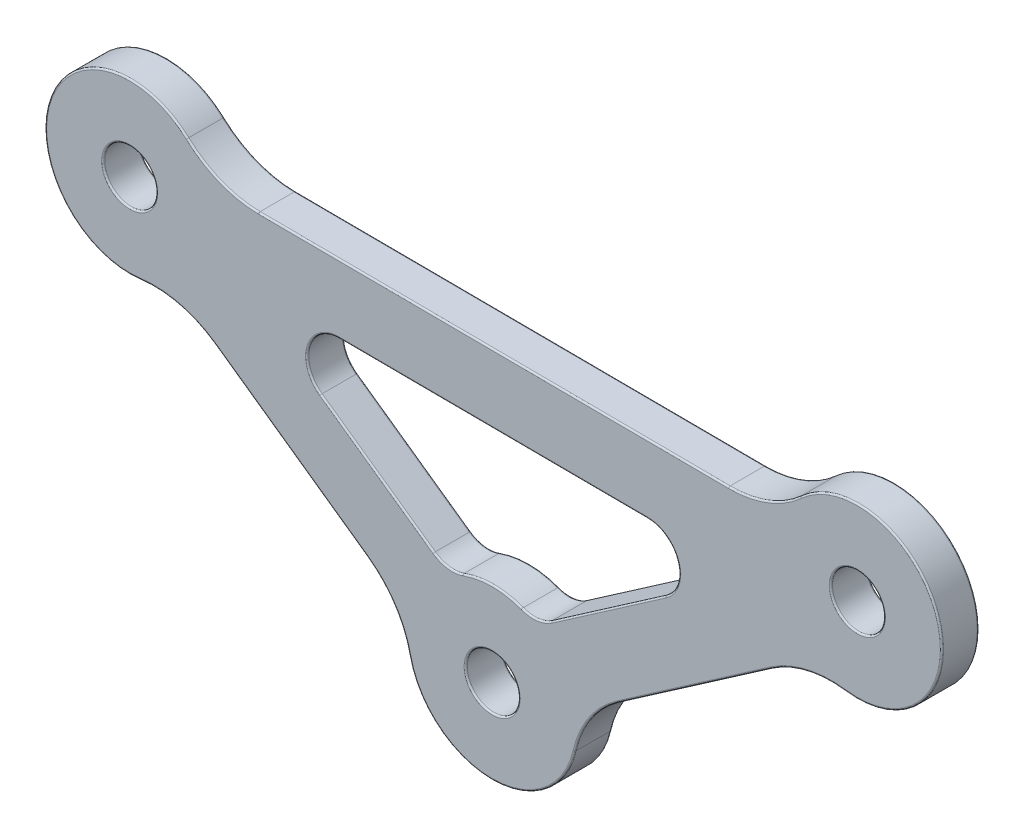
SolidWorks part; units mm, degrees
ref_plane "Front Plane" through (0, 0, 0) normal (0, 0, 1) x (1, 0, 0)
ref_plane "Top Plane" through (0, 0, 0) normal (0, 1, 0) x (1, 0, 0)
ref_plane "Right Plane" through (0, 0, 0) normal (1, 0, 0) x (0, 0, -1)
sketch "Sketch1" plane through (0, 0, 0) normal (0, 0, 1) x (1, 0, 0)
  line L0 (0.465, 228.833) -> (-34.07, 204.9305) construction
  line L1 (0.465, 228.833) -> (-34.07, 204.9305) construction
  line L2 (-68.3427, 229.2077) -> (0.465, 228.833) construction
  line L3 (-68.3427, 229.2077) -> (0.465, 228.833) construction
  line L4 (-34.07, 204.9305) -> (-68.3427, 229.2077) construction
  line L5 (-34.07, 204.9305) -> (-68.3427, 229.2077) construction
  circle A0 centre (-68.3427, 229.2077) radius 8
  circle A1 centre (-68.3427, 229.2077) radius 2.5
  circle A2 centre (0.465, 228.833) radius 8
  circle A3 centre (0.465, 228.833) radius 2.5
  circle A4 centre (-34.07, 204.9305) radius 8
  circle A5 centre (-34.07, 204.9305) radius 2.5
  dimension "D1" = 16
  dimension "D2" = 5
  dimension "D3" = 5
extrude "Boss-Extrude2" add sketch "Sketch1" against normal blind 3.5
sketch "Sketch2" plane through (0, 0, 0) normal (0, 0, 1) x (1, 0, 0)
  line L0 (-4.4686, 225.4184) -> (-29.1365, 208.3452)
  line L1 (0.465, 228.833) -> (-34.07, 204.9305) construction
  line L2 (-38.9661, 208.3987) -> (-63.4466, 225.7396)
  line L3 (-34.07, 204.9305) -> (-68.3427, 229.2077) construction
  line L4 (-61.4388, 229.1701) -> (-6.4388, 228.8706)
  line L5 (-68.3427, 229.2077) -> (0.465, 228.833) construction
  point P12 (-16.8025, 216.8818)
  point P13 (-33.9388, 229.0204)
  point P14 (-51.2064, 217.0691)
  dimension "D1" = 55
  dimension "D2" = 30
extrude "Extrude-Thin1" add sketch "Sketch2" against normal blind 3.5 thin thin type mid plane wall 6.5
fillet "Fillet1" radius 3 4 edges at (-29.9088, 211.7631, -1.75) (-38.1566, 211.808, -1.75) (-58.0529, 225.9016, -1.75) (-9.8602, 225.6392, -1.75)
fillet "Fillet2" radius 10 6 edges at (-64.2562, 222.3302, -1.75) (-41.9138, 206.5039, -1.75) (-3.6962, 222.0004, -1.75) (-26.2096, 206.4184, -1.75) (-6.8273, 232.1228, -1.75) (-61.015, 232.4179, -1.75)
fillet "Fillet3" radius 0.15 46 edges at (2.965, 228.833, -3.5) (-31.57, 204.9305, -3.5) (-65.8427, 229.2077, -3.5) (-16.5252, 223.5776, -3.5) (-23.0802, 216.4893, -3.5) (-23.0802, 216.4893, 0) (-29.8183, 212.2435, -3.5) (-34.0265, 212.9304, -3.5) (-38.2419, 212.2894, -3.5) (-44.9333, 216.6083, 0) (-44.9333, 216.6083, -3.5) (-51.4108, 223.7676, -3.5) (-33.9565, 225.7704, 0) (-33.9565, 225.7704, -3.5) (-63.6383, 221.0555, -3.5) (-53.085, 214.4171, 0) (-53.085, 214.4171, -3.5) (-43.3213, 206.6639, -3.5) (-34.1136, 196.9306, -3.5) (-24.8005, 206.563, -3.5) (-14.9529, 214.2094, -3.5) (-14.9529, 214.2094, 0) (-4.3279, 220.7325, -3.5) (8.1078, 231.1971, -3.5) (-8.0645, 232.8126, -3.5) (-33.9211, 232.2703, 0) (-33.9211, 232.2703, -3.5) (-59.7704, 233.0942, -3.5) (-75.9592, 231.6549, -3.5) (2.965, 228.833, 0) (-31.57, 204.9305, 0) (-65.8427, 229.2077, 0) (-29.8183, 212.2435, 0) (-16.5252, 223.5776, 0) (-51.4108, 223.7676, 0) (-38.2419, 212.2894, 0) (-34.0265, 212.9304, 0) (-8.0645, 232.8126, 0) (8.1078, 231.1971, 0) (-4.3279, 220.7325, 0) (-24.8005, 206.563, 0) (-34.1136, 196.9306, 0) (-43.3213, 206.6639, 0) (-63.6383, 221.0555, 0) (-75.9592, 231.6549, 0) (-59.7704, 233.0942, 0)
